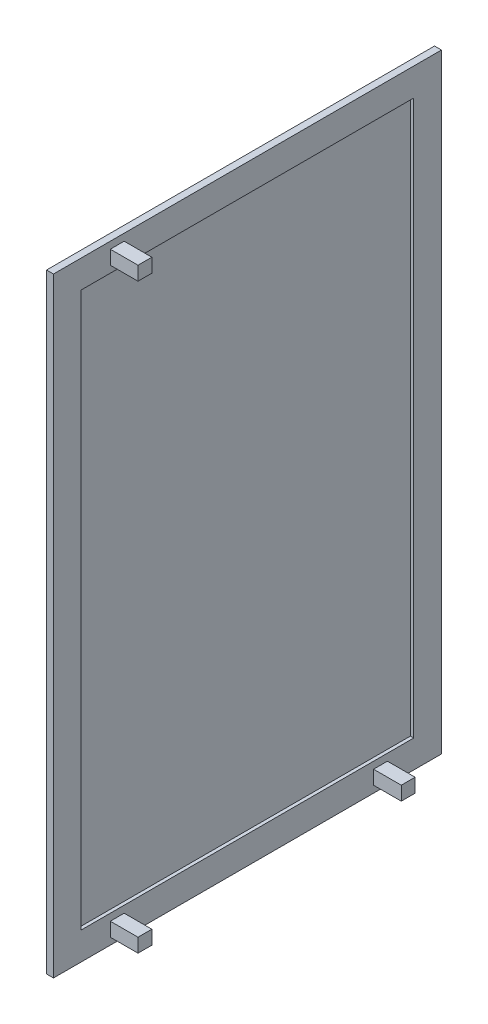
SolidWorks part; units mm, degrees
ref_plane "Front Plane" through (0, 0, 0) normal (0, 0, 1) x (1, 0, 0)
ref_plane "Top Plane" through (0, 0, 0) normal (0, 1, 0) x (1, 0, 0)
ref_plane "Right Plane" through (0, 0, 0) normal (1, 0, 0) x (0, 0, -1)
sketch "Sketch1" plane through (0, 0, 0) normal (1, 0, 0) x (0, 0, -1)
  line L1 (0, 0) -> (70, 0)
  line L2 (0, 0) -> (0, 110)
  line L3 (0, 110) -> (70, 110)
  line L4 (70, 0) -> (70, 110)
  dimension "D1" = 110
  dimension "D2" = 70
extrude "Boss-Extrude1" add sketch "Sketch1" along normal blind 1.25
sketch "Sketch2" plane through (1.25, 0, 0) normal (1, 0, 0) x (0, 0, -1)
  line L0 (0, 110) -> (0, 0) construction
  line L1 (10.25, 108.75) -> (12.75, 108.75)
  line L2 (10.25, 108.75) -> (10.25, 106.25)
  line L3 (10.25, 106.25) -> (12.75, 106.25)
  line L4 (12.75, 108.75) -> (12.75, 106.25)
  line L5 (70, 110) -> (0, 110) construction
  line L6 (0, 0) -> (70, 0) construction
  line L7 (10.25, 3.75) -> (12.75, 3.75)
  line L8 (10.25, 3.75) -> (10.25, 1.25)
  line L9 (10.25, 1.25) -> (12.75, 1.25)
  line L10 (12.75, 3.75) -> (12.75, 1.25)
  line L12 (57.75, 3.75) -> (60.25, 3.75)
  line L13 (57.75, 3.75) -> (57.75, 1.25)
  line L14 (57.75, 1.25) -> (60.25, 1.25)
  line L15 (60.25, 3.75) -> (60.25, 1.25)
  point P12 (10.25, 2.5)
  dimension "D1" = 2.5
  dimension "D2" = 2.5
  dimension "D3" = 10.25
  dimension "D4" = 1.25
  dimension "D5" = 2.5
  dimension "D6" = 2.5
  dimension "D7" = 10.25
  dimension "D8" = 1.25
  dimension "D9" = 2.5
  dimension "D10" = 2.5
  dimension "D11" = 1.25
  dimension "D12" = 45
extrude "Boss-Extrude2" add sketch "Sketch2" along normal blind 5
sketch "Sketch3" plane through (1.25, 0, 0) normal (1, 0, 0) x (0, 0, -1)
  line L0 (0, 110) -> (0, 0) construction
  line L1 (5, 105) -> (65, 105)
  line L2 (5, 105) -> (5, 5)
  line L3 (5, 5) -> (65, 5)
  line L4 (65, 105) -> (65, 5)
  line L5 (70, 110) -> (0, 110) construction
  line L6 (70, 0) -> (70, 110) construction
  line L7 (0, 0) -> (70, 0) construction
  dimension "D1" = 5
  dimension "D2" = 5
  dimension "D3" = 5
  dimension "D4" = 5
extrude "Cut-Extrude1" cut sketch "Sketch3" against normal blind 0.6
